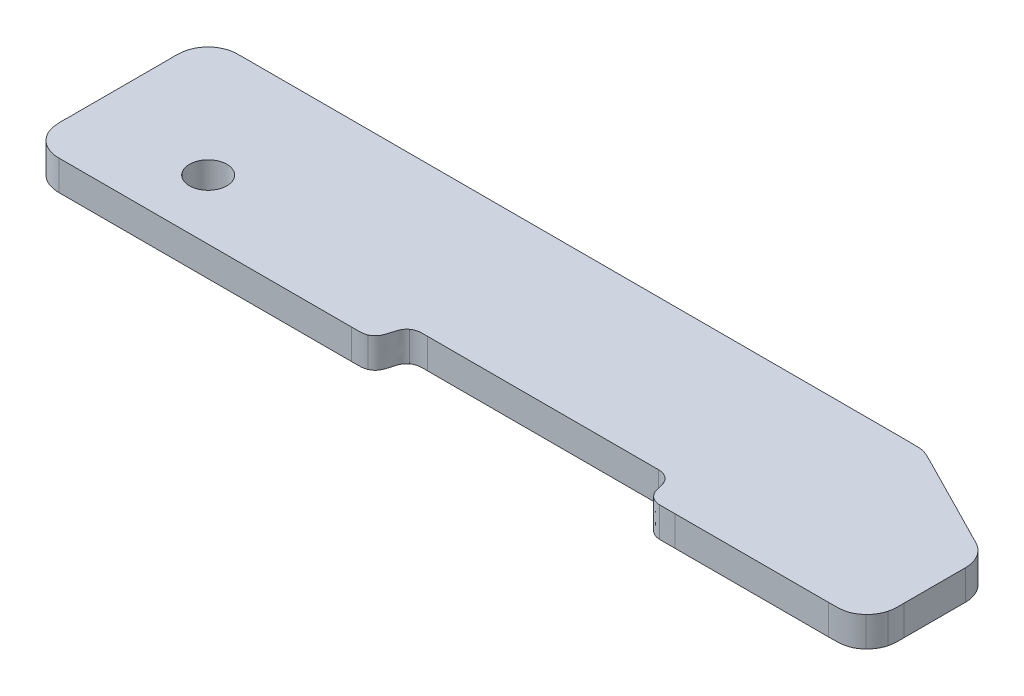
SolidWorks part; units mm, degrees
ref_plane "Front Plane" through (0, 0, 0) normal (0, 0, 1) x (1, 0, 0)
ref_plane "Top Plane" through (0, 0, 0) normal (0, 1, 0) x (1, 0, 0)
ref_plane "Right Plane" through (0, 0, 0) normal (1, 0, 0) x (0, 0, -1)
sketch "Imported Profile" plane through (0, 0, 0) normal (0, 1, 0) x (1, 0, 0)
  spline S0 degree 3 poles (178.0582, 21.1546) (178.0578, 16.8138) (178.0575, 12.466) (178.0571, 8.1183) knots 0 0 0 0 1 1 1 1
  spline S1 degree 3 poles (178.0571, 8.1183) (178.0575, 7.0503) (178.1268, 5.9962) (177.8377, 4.935) knots 0 0 0 0 1 1 1 1
  spline S2 degree 3 poles (177.8377, 4.935) (177.5208, 3.7568) (176.9764, 2.8473) (176.1014, 1.9998) knots 0 0 0 0 1 1 1 1
  spline S3 degree 3 poles (176.1014, 1.9998) (174.117, 0.105) (172.3462, 0.2359) (169.9209, 0.2359) knots 0 0 0 0 1 1 1 1
  spline S4 degree 3 poles (169.9209, 0.2359) (161.2323, 0.2359) (152.5369, 0.2359) (143.8484, 0.2359) knots 0 0 0 0 1 1 1 1
  spline S5 degree 3 poles (143.8484, 0.2359) (141.6642, 0.2359) (139.4869, 0.2359) (137.3096, 0.2359) knots 0 0 0 0 1 1 1 1
  spline S6 degree 3 poles (137.3096, 0.2359) (136.2209, 0.2359) (135.1392, 0.2014) (134.0505, 0.2359) knots 0 0 0 0 1 1 1 1
  spline S7 degree 3 poles (134.0505, 0.2359) (132.8999, 0.2704) (131.8595, 0.918) (131.3289, 1.9377) knots 0 0 0 0 1 1 1 1
  spline S8 degree 3 poles (131.3289, 1.9377) (130.819, 2.9161) (130.8811, 4.0324) (130.316, 5.0039) knots 0 0 0 0 1 1 1 1
  spline S9 degree 3 poles (130.316, 5.0039) (129.7373, 6.003) (128.6831, 6.5817) (127.5324, 6.5817) knots 0 0 0 0 1 1 1 1
  spline S10 degree 3 poles (127.5324, 6.5817) (125.3551, 6.5817) (123.1778, 6.5817) (121.0005, 6.5817) knots 0 0 0 0 1 1 1 1
  spline S11 degree 3 poles (121.0005, 6.5817) (112.2844, 6.5817) (103.5752, 6.5817) (94.8591, 6.5817) knots 0 0 0 0 1 1 1 1
  spline S12 degree 3 poles (94.8591, 6.5817) (90.5045, 6.5817) (86.143, 6.5817) (81.7815, 6.5817) knots 0 0 0 0 1 1 1 1
  spline S13 degree 3 poles (81.7815, 6.5817) (80.6929, 6.5817) (79.6042, 6.5817) (78.5156, 6.5817) knots 0 0 0 0 1 1 1 1
  spline S14 degree 3 poles (78.5156, 6.5817) (77.3994, 6.5817) (76.3727, 6.7195) (75.3461, 5.9685) knots 0 0 0 0 1 1 1 1
  spline S15 degree 3 poles (75.3461, 5.9685) (73.3755, 4.5285) (74.5055, 1.6759) (71.963, 0.5184) knots 0 0 0 0 1 1 1 1
  spline S16 degree 3 poles (71.963, 0.5184) (71.1224, 0.1325) (69.5721, 0.2359) (68.7315, 0.2359) knots 0 0 0 0 1 1 1 1
  spline S17 degree 3 poles (68.7315, 0.2359) (67.6429, 0.2359) (66.5542, 0.2359) (65.4656, 0.2359) knots 0 0 0 0 1 1 1 1
  spline S18 degree 3 poles (65.4656, 0.2359) (63.2883, 0.2359) (61.1041, 0.2359) (58.9268, 0.2359) knots 0 0 0 0 1 1 1 1
  spline S19 degree 3 poles (58.9268, 0.2359) (54.5653, 0.2359) (50.2107, 0.2359) (45.8492, 0.2359) knots 0 0 0 0 1 1 1 1
  spline S20 degree 3 poles (45.8492, 0.2359) (37.1538, 0.2359) (28.4515, 0.2359) (19.7492, 0.2359) knots 0 0 0 0 1 1 1 1
  spline S21 degree 3 poles (19.7492, 0.2359) (15.4014, 0.2359) (11.0468, 0.2359) (6.6991, 0.2359) knots 0 0 0 0 1 1 1 1
  spline S22 degree 3 poles (6.6991, 0.2359) (4.3634, 0.2359) (2.2618, 1.3865) (1.0905, 3.4329) knots 0 0 0 0 1 1 1 1
  spline S23 degree 3 poles (1.0905, 3.4329) (-0.0326, 5.4035) (0.2568, 7.8082) (0.2568, 9.8201) knots 0 0 0 0 1 1 1 1
  spline S24 degree 3 poles (0.2568, 9.8201) (0.2568, 14.1678) (0.2568, 18.5156) (0.2568, 22.8564) knots 0 0 0 0 1 1 1 1
  spline S25 degree 3 poles (0.2568, 22.8564) (0.2568, 25.0337) (0.2568, 27.2041) (0.2568, 29.3745) knots 0 0 0 0 1 1 1 1
  spline S26 degree 3 poles (0.2568, 29.3745) (0.2568, 31.6) (-0.0119, 33.6464) (1.4833, 35.6859) knots 0 0 0 0 1 1 1 1
  spline S27 degree 3 poles (1.4833, 35.6859) (2.2136, 36.685) (3.0611, 37.3464) (4.198, 37.815) knots 0 0 0 0 1 1 1 1
  spline S28 degree 3 poles (4.198, 37.815) (5.2453, 38.2422) (6.2788, 38.2835) (7.3675, 38.2835) knots 0 0 0 0 1 1 1 1
  spline S29 degree 3 poles (7.3675, 38.2835) (9.5379, 38.2835) (11.7083, 38.2835) (13.8856, 38.2835) knots 0 0 0 0 1 1 1 1
  spline S30 degree 3 poles (13.8856, 38.2835) (18.2264, 38.2835) (22.5741, 38.2835) (26.9218, 38.2835) knots 0 0 0 0 1 1 1 1
  spline S31 degree 3 poles (26.9218, 38.2835) (44.4092, 38.2835) (61.8964, 38.2835) (79.3906, 38.2835) knots 0 0 0 0 1 1 1 1
  spline S32 degree 3 poles (79.3906, 38.2835) (96.8573, 38.2835) (114.3308, 38.2835) (131.7975, 38.2835) knots 0 0 0 0 1 1 1 1
  spline S33 degree 3 poles (131.7975, 38.2835) (136.1589, 38.2835) (140.5273, 38.2835) (144.8888, 38.2835) knots 0 0 0 0 1 1 1 1
  spline S34 degree 3 poles (144.8888, 38.2835) (145.4745, 38.2835) (150.8419, 38.304) (151.4345, 38.2216) knots 0 0 0 0 1 1 1 1
  spline S35 degree 3 poles (151.4345, 38.2216) (152.5645, 38.063) (153.5015, 37.5601) (154.48, 37.0571) knots 0 0 0 0 1 1 1 1
  spline S36 degree 3 poles (154.48, 37.0571) (155.4515, 36.5679) (156.423, 36.0718) (157.3945, 35.5757) knots 0 0 0 0 1 1 1 1
  spline S37 degree 3 poles (157.3945, 35.5757) (161.2875, 33.5914) (165.1735, 31.6139) (169.0665, 29.6295) knots 0 0 0 0 1 1 1 1
  spline S38 degree 3 poles (169.0665, 29.6295) (170.038, 29.1334) (171.0095, 28.6373) (171.981, 28.1412) knots 0 0 0 0 1 1 1 1
  spline S39 degree 3 poles (171.981, 28.1412) (172.9526, 27.652) (173.9379, 27.1973) (174.8818, 26.6529) knots 0 0 0 0 1 1 1 1
  spline S40 degree 3 poles (174.8818, 26.6529) (176.8455, 25.523) (178.0582, 23.4214) (178.0582, 21.1546) knots 0 0 0 0 1 1 1 1
  spline S41 degree 3 poles (29.6228, 12.9345) (29.6228, 10.7434) (27.8451, 8.9657) (25.6541, 8.9657) knots 0 0 0 0 1 1 1 1
  spline S42 degree 3 poles (25.6541, 8.9657) (23.463, 8.9657) (21.6853, 10.7434) (21.6853, 12.9345) knots 0 0 0 0 1 1 1 1
  spline S43 degree 3 poles (21.6853, 12.9345) (21.6853, 15.1256) (23.463, 16.9032) (25.6541, 16.9032) knots 0 0 0 0 1 1 1 1
  spline S44 degree 3 poles (25.6541, 16.9032) (27.8451, 16.9032) (29.6228, 15.1256) (29.6228, 12.9345) knots 0 0 0 0 1 1 1 1
sketch "Sketch4" plane through (0, 0, 0) normal (0, 1, 0) x (1, 0, 0)
  circle A0 centre (25.6541, 12.9345) radius 3.9688
  spline S0 degree 3 poles (-1370.1409, 1323.9207) (1038.8939, -923.7451) (-712.4339, 988.9517) (1696.6083, -1258.7214) knots -41.774564 -41.774564 -41.774564 -41.774564 42.774639 42.774639 42.774639 42.774639 only from (157.3945, 35.5757) to (169.0665, 29.6295) construction
  spline S1 degree 3 poles (376.0605, 1875.4206) (-1479.5997, -1082.3544) (1829.0874, 1138.1816) (-51.3256, -1816.4188) knots -369.840284 -369.840284 -369.840284 -369.840284 371.612933 371.612933 371.612933 371.612933 only from (169.0665, 29.6295) to (171.981, 28.1412) construction
  spline S2 degree 3 poles (908.269, 1887.0169) (-659.8258, -1783.9957) (1006.9937, 1838.9417) (-567.5164, -1829.9023) knots -24.219115 -24.219115 -24.219115 -24.219115 24.76741 24.76741 24.76741 24.76741 only from (171.981, 28.1412) to (174.8818, 26.6529) construction
  spline S3 degree 3 poles (634.5941, -1913.7013) (-663.7986, 1873.0389) (1345.8725, -1636.8189) (-1263.0141, 1399.4192) knots -12.393463 -12.393463 -12.393463 -12.393463 13.40497 13.40497 13.40497 13.40497 only from (174.8818, 26.6529) to (178.0582, 21.1546) construction
  spline S4 degree 3 poles (177.8889, -1978.7637) (178.3368, 3312.0916) (177.7768, -3302.3891) (178.2264, 2008.1061) knots -74.483894 -74.483894 -74.483894 -74.483894 76.608418 76.608418 76.608418 76.608418 only from (178.0582, 21.1546) to (178.0571, 8.1183) construction
  spline S5 degree 3 poles (2171.4545, 166.8586) (-1816.6914, -74.7286) (2173.4037, 84.1055) (-1817.1039, -134.2335) knots -16.54842 -16.54842 -16.54842 -16.54842 16.876064 16.876064 16.876064 16.876064 only from (178.0571, 8.1183) to (177.8377, 4.935) construction
  spline S6 degree 3 poles (709.4157, 1930.8999) (-539.7061, -1730.6163) (1128.2343, 1617.8505) (-1058.8853, -1567.9445) knots -19.565605 -19.565605 -19.565605 -19.565605 20.7495 20.7495 20.7495 20.7495 only from (177.8377, 4.935) to (176.1014, 1.9998) construction
  spline S7 degree 3 poles (833.5382, 1890.7975) (-498.1038, -1848.355) (931.456, 1807.4864) (-764.8748, -1766.3119) knots -8.63166 -8.63166 -8.63166 -8.63166 10.296247 10.296247 10.296247 10.296247 only from (176.1014, 1.9998) to (169.9209, 0.2359) construction
  spline S8 degree 3 poles (-1830.031, 0.2359) (4381.8556, 0.2359) (-4068.1572, 0.2359) (2143.7916, 0.2359) knots -63.871392 -63.871392 -63.871392 -63.871392 64.873514 64.873514 64.873514 64.873514 only from (169.9209, 0.2359) to (143.8484, 0.2359) construction
  spline S9 degree 3 poles (2143.7844, 0.2359) (-1331.6123, 0.2359) (1604.7294, 0.2359) (-1862.6509, 0.2359) knots -60.473146 -60.473146 -60.473146 -60.473146 62.39629 62.39629 62.39629 62.39629 only from (143.8484, 0.2359) to (137.3096, 0.2359) construction
  spline S10 degree 3 poles (490.5198, -1967.6601) (-98.9506, 1969.9859) (368.1575, -1970.1717) (-208.4723, 1970.0419) knots -26.362878 -26.362878 -26.362878 -26.362878 27.038245 27.038245 27.038245 27.038245 only from (137.3096, 0.2359) to (134.0505, 0.2359) construction
  spline S11 degree 3 poles (-1291.7134, 1397.3141) (1777.1165, -1170.1098) (-1670.4385, 908.9937) (2031.8713, -608.5517) knots -15.752288 -15.752288 -15.752288 -15.752288 16.705304 16.705304 16.705304 16.705304 only from (134.0505, 0.2359) to (131.3289, 1.9377) construction
  spline S12 degree 3 poles (2085.5986, 426.3777) (-1812.936, -467.9319) (2074.8556, 473.9409) (-1824.4844, -417.1797) knots -11.275893 -11.275893 -11.275893 -11.275893 12.231094 12.231094 12.231094 12.231094 only from (131.3289, 1.9377) to (130.316, 5.0039) construction
  spline S13 degree 3 poles (-1843.081, 303.1764) (2044.6357, -616.4683) (-1660.8929, 930.7797) (1720.8277, -1194.9113) knots -16.246574 -16.246574 -16.246574 -16.246574 17.589455 17.589455 17.589455 17.589455 only from (130.316, 5.0039) to (127.5324, 6.5817) construction
  spline S14 degree 3 poles (-1872.393, 6.5817) (6146.2332, 6.5817) (-5897.6947, 6.5817) (2120.9175, 6.5817) knots -461.690422 -461.690422 -461.690422 -461.690422 462.690096 462.690096 462.690096 462.690096 only from (127.5324, 6.5817) to (121.0005, 6.5817) construction
  spline S15 degree 3 poles (2120.9851, 6.5817) (-481.4997, 6.5817) (697.3592, 6.5817) (-1905.1308, 6.5817) knots -40.349467 -40.349467 -40.349467 -40.349467 41.349524 41.349524 41.349524 41.349524 only from (121.0005, 6.5817) to (94.8591, 6.5817) construction
  spline S16 degree 3 poles (-1905.0989, 6.5817) (3392.2369, 6.5817) (-3235.2001, 6.5817) (2081.7359, 6.5817) knots -74.617885 -74.617885 -74.617885 -74.617885 76.742175 76.742175 76.742175 76.742175 only from (94.8591, 6.5817) to (81.7815, 6.5817) construction
  spline S17 degree 3 poles (-1918.1787, 6.5817) (3831.2809, 6.5817) (-3670.9821, 6.5817) (2078.4727, 6.5817) knots -402.015798 -402.015798 -402.015798 -402.015798 403.015652 403.015652 403.015652 403.015652 only from (81.7815, 6.5817) to (78.5156, 6.5817) construction
  spline S18 degree 3 poles (328.2274, 1990.6477) (-93.8184, -1981.2991) (226.0489, 1997.3818) (-100.5912, -1986.1981) knots -12.323971 -12.323971 -12.323971 -12.323971 12.610585 12.610585 12.610585 12.610585 only from (78.5156, 6.5817) to (75.3461, 5.9685) construction
  spline S19 degree 3 poles (1909.0335, -792.0449) (-1746.7322, 853.3885) (1894.4289, -847.3372) (-1760.6043, 801.1145) knots -6.000439 -6.000439 -6.000439 -6.000439 6.915353 6.915353 6.915353 6.915353 only from (75.3461, 5.9685) to (71.963, 0.5184) construction
  spline S20 degree 3 poles (-1741.4222, 843.5146) (1951.0212, -802.4628) (-1827.6146, 763.5106) (1932.5612, -724.841) knots -10.425283 -10.425283 -10.425283 -10.425283 11.524314 11.524314 11.524314 11.524314 only from (71.963, 0.5184) to (68.7315, 0.2359) construction
  spline S21 degree 3 poles (2068.7081, 0.2359) (-494.9121, 0.2359) (625.9794, 0.2359) (-1934.5108, 0.2359) knots -330.094334 -330.094334 -330.094334 -330.094334 331.813063 331.813063 331.813063 331.813063 only from (68.7315, 0.2359) to (65.4656, 0.2359) construction
  spline S22 degree 3 poles (-1934.4558, 0.2359) (2544.0676, 0.2359) (-2419.691, 0.2359) (2058.8868, 0.2359) knots -55.124015 -55.124015 -55.124015 -55.124015 56.124335 56.124335 56.124335 56.124335 only from (65.4656, 0.2359) to (58.9268, 0.2359) construction
  spline S23 degree 3 poles (2058.9124, 0.2359) (-1141.0787, 0.2359) (1245.8467, 0.2359) (-1954.0877, 0.2359) knots -46.140285 -46.140285 -46.140285 -46.140285 47.139812 47.139812 47.139812 47.139812 only from (58.9268, 0.2359) to (45.8492, 0.2359) construction
  spline S24 degree 3 poles (-1954.0586, 0.2359) (4959.9478, 0.2359) (-4936.8779, 0.2359) (2019.6311, 0.2359) knots -83.969481 -83.969481 -83.969481 -83.969481 86.191752 86.191752 86.191752 86.191752 only from (45.8492, 0.2359) to (19.7492, 0.2359) construction
  spline S25 degree 3 poles (-1980.2129, 0.2359) (3024.9489, 0.2359) (-2998.4869, 0.2359) (2006.6319, 0.2359) knots -58.007247 -58.007247 -58.007247 -58.007247 59.007019 59.007019 59.007019 59.007019 only from (19.7492, 0.2359) to (6.6991, 0.2359) construction
  spline S26 degree 3 poles (-1518.6587, 1280.0571) (1804.2894, -892.1883) (-1949.0224, 475.8394) (1993.1986, -27.5117) knots -13.599929 -13.599929 -13.599929 -13.599929 14.087522 14.087522 14.087522 14.087522 only from (6.6991, 0.2359) to (1.0905, 3.4329) construction
  spline S27 degree 3 poles (1850.5432, 762.9152) (-1832.6938, -877.3868) (1813.9623, 937.6913) (-1792.4897, -876.4778) knots -9.455497 -9.455497 -9.455497 -9.455497 11.007676 11.007676 11.007676 11.007676 only from (1.0905, 3.4329) to (0.2568, 9.8201) construction
  spline S28 degree 3 poles (0.2568, 2009.7703) (0.2568, -3300.6804) (0.2568, 3313.8414) (0.2568, -1977.1345) knots -75.608062 -75.608062 -75.608062 -75.608062 75.484586 75.484586 75.484586 75.484586 only from (0.2568, 9.8201) to (0.2568, 22.8564) construction
  spline S29 degree 3 poles (0.2568, -1977.0858) (0.2568, 1498.0415) (0.2568, -1437.7248) (0.2568, 2029.2923) knots -60.694704 -60.694704 -60.694704 -60.694704 62.624087 62.624087 62.624087 62.624087 only from (0.2568, 22.8564) to (0.2568, 29.3745) construction
  spline S30 degree 3 poles (-1979.6988, -248.5886) (1985.873, 192.3153) (-1989.6613, -101.2351) (1993.0338, 217.8919) knots -9.782615 -9.782615 -9.782615 -9.782615 10.068378 10.068378 10.068378 10.068378 only from (0.2568, 29.3745) to (1.4833, 35.6859) construction
  spline S31 degree 3 poles (-1232.7755, -1535.103) (1340.6323, 1343.5524) (-1511.5406, -1057.7752) (1768.3466, 974.3779) knots -19.756295 -19.756295 -19.756295 -19.756295 20.879982 20.879982 20.879982 20.879982 only from (1.4833, 35.6859) to (4.198, 37.815) construction
  spline S32 degree 3 poles (-383.1861, -1924.2448) (358.5547, 1991.6677) (-381.6585, -1905.6519) (513.4478, 1972.461) knots -16.73895 -16.73895 -16.73895 -16.73895 18.892251 18.892251 18.892251 18.892251 only from (4.198, 37.815) to (7.3675, 38.2835) construction
  spline S33 degree 3 poles (-1992.578, 38.2835) (1476.3701, 38.2835) (-1463.0889, 38.2835) (2013.8636, 38.2835) knots -61.407639 -61.407639 -61.407639 -61.407639 61.491697 61.491697 61.491697 61.491697 only from (7.3675, 38.2835) to (13.8856, 38.2835) construction
  spline S34 degree 3 poles (2013.8663, 38.2835) (-3282.4938, 38.2835) (3342.9854, 38.2835) (-1973.0515, 38.2835) knots -74.794721 -74.794721 -74.794721 -74.794721 76.92726 76.92726 76.92726 76.92726 only from (13.8856, 38.2835) to (26.9218, 38.2835) construction
  spline S35 degree 3 poles (-1973.0671, 38.2835) (-282.1228, 38.2835) (366.949, 38.2835) (2079.3673, 38.2835) knots -33.258534 -33.258534 -33.258534 -33.258534 33.951426 33.951426 33.951426 33.951426 only from (26.9218, 38.2835) to (79.3906, 38.2835) construction
  spline S36 degree 3 poles (79.3798, 38.2835) (-4648.3375, 38.2835) (6497.4658, 38.2835) (-1868.1201, 38.2835) knots -60.949289 -60.949289 -60.949289 -60.949289 76.032141 76.032141 76.032141 76.032141 only from (79.3906, 38.2835) to (131.7975, 38.2835) construction
  spline S37 degree 3 poles (2131.7334, 38.2835) (-2877.58, 38.2835) (3154.3213, 38.2835) (-1855.0887, 38.2835) knots -58.064419 -58.064419 -58.064419 -58.064419 59.06678 59.06678 59.06678 59.06678 only from (131.7975, 38.2835) to (144.8888, 38.2835) construction
  spline S38 degree 3 poles (2144.6774, 60.5049) (-1919.6384, 13.355) (2215.9334, 66.1673) (-1848.2672, 7.1957) knots -5.485793 -5.485793 -5.485793 -5.485793 6.486432 6.486432 6.486432 6.486432 only from (144.8888, 38.2835) to (151.4345, 38.2216) construction
  spline S39 degree 3 poles (-992.6085, -1602.0212) (1251.1464, 1698.4933) (-958.1323, -1612.5578) (1348.0175, 1641.3866) knots -15.910235 -15.910235 -15.910235 -15.910235 17.791712 17.791712 17.791712 17.791712 only from (151.4345, 38.2216) to (154.48, 37.0571) construction
  spline S40 degree 3 poles (-53.3601, -1948.7709) (107.4351, 2153.4705) (207.1509, -2082.6357) (368.8715, 2020.8147) knots -66.150823 -66.150823 -66.150823 -66.150823 68.16056 68.16056 68.16056 68.16056 only from (154.48, 37.0571) to (157.3945, 35.5757) construction
  spline S41 degree 3 poles (157.3945, 35.5757) (161.2875, 33.5914) (165.1735, 31.6139) (169.0665, 29.6295) knots 0 0 0 0 1 1 1 1
  spline S42 degree 3 poles (169.0665, 29.6295) (170.038, 29.1334) (171.0095, 28.6373) (171.981, 28.1412) knots 0 0 0 0 1 1 1 1
  spline S43 degree 3 poles (171.981, 28.1412) (172.9526, 27.652) (173.9379, 27.1973) (174.8818, 26.6529) knots 0 0 0 0 1 1 1 1
  spline S44 degree 3 poles (174.8818, 26.6529) (176.8457, 25.5229) (178.0584, 23.4211) (178.0582, 21.154) knots 0 0 0 0 1.000079 1.000079 1.000079 1.000079
  spline S45 degree 3 poles (178.0582, 21.154) (178.0578, 16.8134) (178.0575, 12.4659) (178.0571, 8.1183) knots 0.000041 0.000041 0.000041 0.000041 1 1 1 1
  spline S46 degree 3 poles (178.0571, 8.1183) (178.0575, 7.0503) (178.1268, 5.9962) (177.8377, 4.935) knots 0 0 0 0 1 1 1 1
  spline S47 degree 3 poles (177.8377, 4.935) (177.5208, 3.7568) (176.9764, 2.8473) (176.1014, 1.9998) knots 0 0 0 0 1 1 1 1
  spline S48 degree 3 poles (176.1014, 1.9998) (174.117, 0.105) (172.3462, 0.2359) (169.9209, 0.2359) knots 0 0 0 0 1 1 1 1
  spline S49 degree 3 poles (169.9209, 0.2359) (161.2323, 0.2359) (152.5369, 0.2359) (143.8484, 0.2359) knots 0 0 0 0 1 1 1 1
  spline S50 degree 3 poles (143.8484, 0.2359) (141.6642, 0.2359) (139.4869, 0.2359) (137.3096, 0.2359) knots 0 0 0 0 1 1 1 1
  spline S51 degree 3 poles (137.3096, 0.2359) (136.2209, 0.2359) (135.1392, 0.2014) (134.0505, 0.2359) knots 0 0 0 0 1 1 1 1
  spline S52 degree 3 poles (134.0505, 0.2359) (132.8999, 0.2704) (131.8595, 0.918) (131.3289, 1.9377) knots 0 0 0 0 1 1 1 1
  spline S53 degree 3 poles (131.3289, 1.9377) (130.819, 2.9161) (130.8811, 4.0324) (130.316, 5.0039) knots 0 0 0 0 1 1 1 1
  spline S54 degree 3 poles (130.316, 5.0039) (129.7373, 6.003) (128.6831, 6.5817) (127.5324, 6.5817) knots 0 0 0 0 1 1 1 1
  spline S55 degree 3 poles (127.5324, 6.5817) (125.3551, 6.5817) (123.1778, 6.5817) (121.0005, 6.5817) knots 0 0 0 0 1 1 1 1
  spline S56 degree 3 poles (121.0005, 6.5817) (112.2844, 6.5817) (103.5752, 6.5817) (94.8591, 6.5817) knots 0 0 0 0 1 1 1 1
  spline S57 degree 3 poles (94.8591, 6.5817) (90.5045, 6.5817) (86.143, 6.5817) (81.7815, 6.5817) knots 0 0 0 0 1 1 1 1
  spline S58 degree 3 poles (81.7815, 6.5817) (80.6929, 6.5817) (79.6042, 6.5817) (78.5156, 6.5817) knots 0 0 0 0 1 1 1 1
  spline S59 degree 3 poles (78.5156, 6.5817) (77.3994, 6.5817) (76.3727, 6.7195) (75.3461, 5.9685) knots 0 0 0 0 1 1 1 1
  spline S60 degree 3 poles (75.3461, 5.9685) (73.3755, 4.5285) (74.5055, 1.6759) (71.963, 0.5184) knots 0 0 0 0 1 1 1 1
  spline S61 degree 3 poles (71.963, 0.5184) (71.1224, 0.1325) (69.5721, 0.2359) (68.7315, 0.2359) knots 0 0 0 0 1 1 1 1
  spline S62 degree 3 poles (68.7315, 0.2359) (67.6429, 0.2359) (66.5542, 0.2359) (65.4656, 0.2359) knots 0 0 0 0 1 1 1 1
  spline S63 degree 3 poles (65.4656, 0.2359) (63.2883, 0.2359) (61.1041, 0.2359) (58.9268, 0.2359) knots 0 0 0 0 1 1 1 1
  spline S64 degree 3 poles (58.9268, 0.2359) (54.5653, 0.2359) (50.2107, 0.2359) (45.8492, 0.2359) knots 0 0 0 0 1 1 1 1
  spline S65 degree 3 poles (45.8492, 0.2359) (37.1538, 0.2359) (28.4515, 0.2359) (19.7492, 0.2359) knots 0 0 0 0 1 1 1 1
  spline S66 degree 3 poles (19.7492, 0.2359) (15.4014, 0.2359) (11.0468, 0.2359) (6.6991, 0.2359) knots 0 0 0 0 1 1 1 1
  spline S67 degree 3 poles (6.6991, 0.2359) (4.3634, 0.2359) (2.2618, 1.3865) (1.0905, 3.4329) knots 0 0 0 0 1 1 1 1
  spline S68 degree 3 poles (1.0905, 3.4329) (-0.0326, 5.4035) (0.2568, 7.8082) (0.2568, 9.8201) knots 0 0 0 0 1 1 1 1
  spline S69 degree 3 poles (0.2568, 9.8201) (0.2568, 14.1678) (0.2568, 18.5156) (0.2568, 22.8564) knots 0 0 0 0 1 1 1 1
  spline S70 degree 3 poles (0.2568, 22.8564) (0.2568, 25.0337) (0.2568, 27.2041) (0.2568, 29.3745) knots 0 0 0 0 1 1 1 1
  spline S71 degree 3 poles (0.2568, 29.3745) (0.2568, 31.6) (-0.0119, 33.6464) (1.4833, 35.6859) knots 0 0 0 0 1 1 1 1
  spline S72 degree 3 poles (1.4833, 35.6859) (2.2136, 36.685) (3.0611, 37.3464) (4.198, 37.815) knots 0 0 0 0 1 1 1 1
  spline S73 degree 3 poles (4.198, 37.815) (5.2453, 38.2422) (6.2788, 38.2835) (7.3675, 38.2835) knots 0 0 0 0 1 1 1 1
  spline S74 degree 3 poles (7.3675, 38.2835) (9.5379, 38.2835) (11.7083, 38.2835) (13.8856, 38.2835) knots 0 0 0 0 1 1 1 1
  spline S75 degree 3 poles (13.8856, 38.2835) (18.2264, 38.2835) (22.5741, 38.2835) (26.9218, 38.2835) knots 0 0 0 0 1 1 1 1
  spline S76 degree 3 poles (26.9218, 38.2835) (44.4092, 38.2835) (61.8964, 38.2835) (79.3906, 38.2835) knots 0 0 0 0 1 1 1 1
  spline S77 degree 3 poles (79.3906, 38.2835) (96.8573, 38.2835) (114.3308, 38.2835) (131.7975, 38.2835) knots 0 0 0 0 1 1 1 1
  spline S78 degree 3 poles (131.7975, 38.2835) (136.1589, 38.2835) (140.5273, 38.2835) (144.8888, 38.2835) knots 0 0 0 0 1 1 1 1
  spline S79 degree 3 poles (144.8888, 38.2835) (145.4745, 38.2835) (150.8419, 38.304) (151.4345, 38.2216) knots 0 0 0 0 1 1 1 1
  spline S80 degree 3 poles (151.4345, 38.2216) (152.5645, 38.063) (153.5015, 37.5601) (154.48, 37.0571) knots 0 0 0 0 1 1 1 1
  spline S81 degree 3 poles (154.48, 37.0571) (155.4515, 36.5679) (156.423, 36.0718) (157.3945, 35.5757) knots 0 0 0 0 1 1 1 1
extrude "Boss-Extrude1" add sketch "Sketch4" along normal blind 6.35
